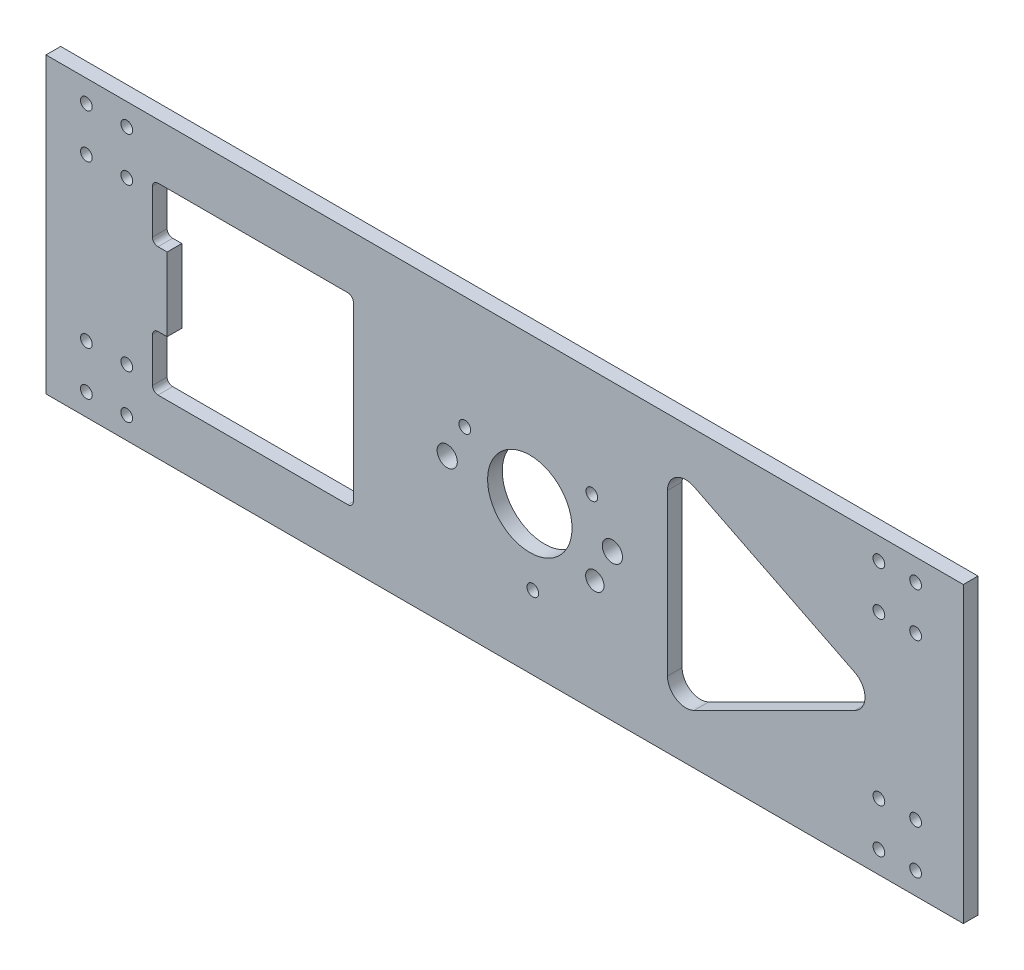
SolidWorks part; units mm, degrees
ref_plane "前视基准面" through (0, 0, 0) normal (0, 0, 1) x (1, 0, 0)
ref_plane "上视基准面" through (0, 0, 0) normal (0, 1, 0) x (1, 0, 0)
ref_plane "右视基准面" through (0, 0, 0) normal (1, 0, 0) x (0, 0, -1)
sketch "草图1" plane through (0, 0, 0) normal (0, 0, 1) x (1, 0, 0)
  line L1 (-88.8431, 86.7208) -> (161.0585, 86.7208)
  line L2 (-88.8431, 86.7208) -> (-88.8431, 6.7208)
  line L3 (-88.8431, 6.7208) -> (161.0585, 6.7208)
  line L4 (161.0585, 86.7208) -> (161.0585, 6.7208)
extrude "凸台-拉伸1" add sketch "草图1" along normal blind 4
sketch "草图2" plane through (0, 0, 4) normal (0, 0, 1) x (1, 0, 0)
  circle A0 centre (20.4585, 46.7208) radius 2.75
  circle A1 centre (65.4585, 46.7208) radius 2.75
  circle A2 centre (42.9585, 46.7208) radius 2.55
extrude "切除-拉伸1" cut sketch "草图2" against normal blind 4
sketch "草图3" plane through (0, 0, 4) normal (0, 0, 1) x (1, 0, 0)
  line L3 (80.4585, 68.6306) -> (80.4585, 24.8109)
  line L4 (87.6946, 20.3388) -> (131.5142, 42.2486)
  line L5 (131.5142, 51.1929) -> (87.6946, 73.1027)
  line L6 (161.0585, 86.7208) -> (-88.8431, 86.7208) construction
  line L7 (-88.8431, 6.7208) -> (161.0585, 6.7208) construction
  circle A1 centre (65.4585, 46.7208) radius 2.75 construction
  arc A2 (131.5142, 42.2486) -> (131.5142, 51.1929) centre (129.2782, 46.7208) ccw
  arc A3 (80.4585, 24.8109) -> (87.6946, 20.3388) centre (85.4585, 24.8109) ccw
  arc A4 (80.4585, 68.6306) -> (87.6946, 73.1027) centre (85.4585, 68.6306) cw
  point P18 (140.4585, 46.7208)
  point P21 (80.4585, 16.7208)
  point P24 (80.4585, 76.7208)
  dimension "D10" = 15
  dimension "D11" = 5
  dimension "D1" = 10
  dimension "D2" = 10
  dimension "D6" = 40
  dimension "D7" = 60
extrude "切除-拉伸2" cut sketch "草图3" against normal blind 10
sketch "草图4" plane through (0, 0, 4) normal (0, 0, 1) x (1, 0, 0)
  line L0 (-88.8431, 46.7208) -> (161.0585, 46.7208) construction
  line L1 (-88.8431, 86.7208) -> (-88.8431, 6.7208) construction
  circle A0 centre (-77.8431, 80.7208) radius 1.6
  circle A1 centre (-77.8431, 68.7208) radius 1.6
  circle A2 centre (-66.8431, 80.7208) radius 1.6
  circle A3 centre (-66.8431, 68.7208) radius 1.6
  circle A4 centre (138.0585, 80.7208) radius 1.6
  circle A5 centre (138.0585, 68.7208) radius 1.6
  circle A6 centre (148.0585, 80.7208) radius 1.6
  circle A7 centre (148.0585, 68.7208) radius 1.6
  circle A8 centre (148.0585, 24.7208) radius 1.6
  circle A9 centre (148.0585, 12.7208) radius 1.6
  circle A10 centre (138.0585, 24.7208) radius 1.6
  circle A11 centre (138.0585, 12.7208) radius 1.6
  circle A12 centre (-66.8431, 24.7208) radius 1.6
  circle A13 centre (-66.8431, 12.7208) radius 1.6
  circle A14 centre (-77.8431, 24.7208) radius 1.6
  circle A15 centre (-77.8431, 12.7208) radius 1.6
  point P36 (-77.8431, 80.7208)
  point P38 (-77.8431, 68.7208)
  point P39 (-66.8431, 80.7208)
  point P41 (-66.8431, 68.7208)
extrude "切除-拉伸3" cut sketch "草图4" against normal blind 5
sketch "草图5" plane through (0, 0, 4) normal (0, 0, 1) x (1, 0, 0)
  line L0 (-59.8431, 62.7208) -> (-59.8431, 86.7208) construction
  line L1 (-59.8431, 71.7208) -> (-5.1153, 71.7208)
  line L2 (-59.8431, 71.7208) -> (-59.8431, 56.7208)
  line L3 (-59.8431, 21.7208) -> (-5.1153, 21.7208)
  line L4 (-5.1153, 71.7208) -> (-5.1153, 21.7208)
  line L5 (161.0585, 86.7208) -> (-88.8431, 86.7208) construction
  line L6 (-88.8431, 6.7208) -> (161.0585, 6.7208) construction
  line L7 (-59.8431, 36.7208) -> (-59.8431, 21.7208)
  line L8 (-59.8431, 56.7208) -> (-55.8431, 56.7208)
  line L10 (-59.8431, 36.7208) -> (-55.8431, 36.7208)
  line L11 (-55.8431, 56.7208) -> (-55.8431, 36.7208)
  dimension "D1" = 15
  dimension "D2" = 15
  dimension "D3" = 4
  dimension "D4" = 15
  dimension "D5" = 15
extrude "切除-拉伸4" cut sketch "草图5" against normal blind 10
fillet "圆角1" radius 1.5 6 edges at (-59.8431, 56.7208, 2) (-59.8431, 36.7208, 2) (-5.1153, 21.7208, 2) (-5.1153, 71.7208, 2) (-59.8431, 71.7208, 2) (-59.8431, 21.7208, 2)
sketch "草图6" plane through (0, 0, 0) normal (0, 0, -1) x (-1, 0, 0)
  circle A0 centre (-25.2449, 56.0067) radius 1.6
  circle A1 centre (-43.7734, 26.7374) radius 1.6
  circle A2 centre (-59.8572, 57.4182) radius 1.6
  circle A3 centre (-60.6721, 37.4348) radius 2.5
  circle A4 centre (-42.9585, 46.7208) radius 11.5
  dimension "D1" = 3.2
  dimension "D2" = 5
  dimension "D3" = 23
extrude "切除-拉伸5" cut sketch "草图6" against normal blind 5
